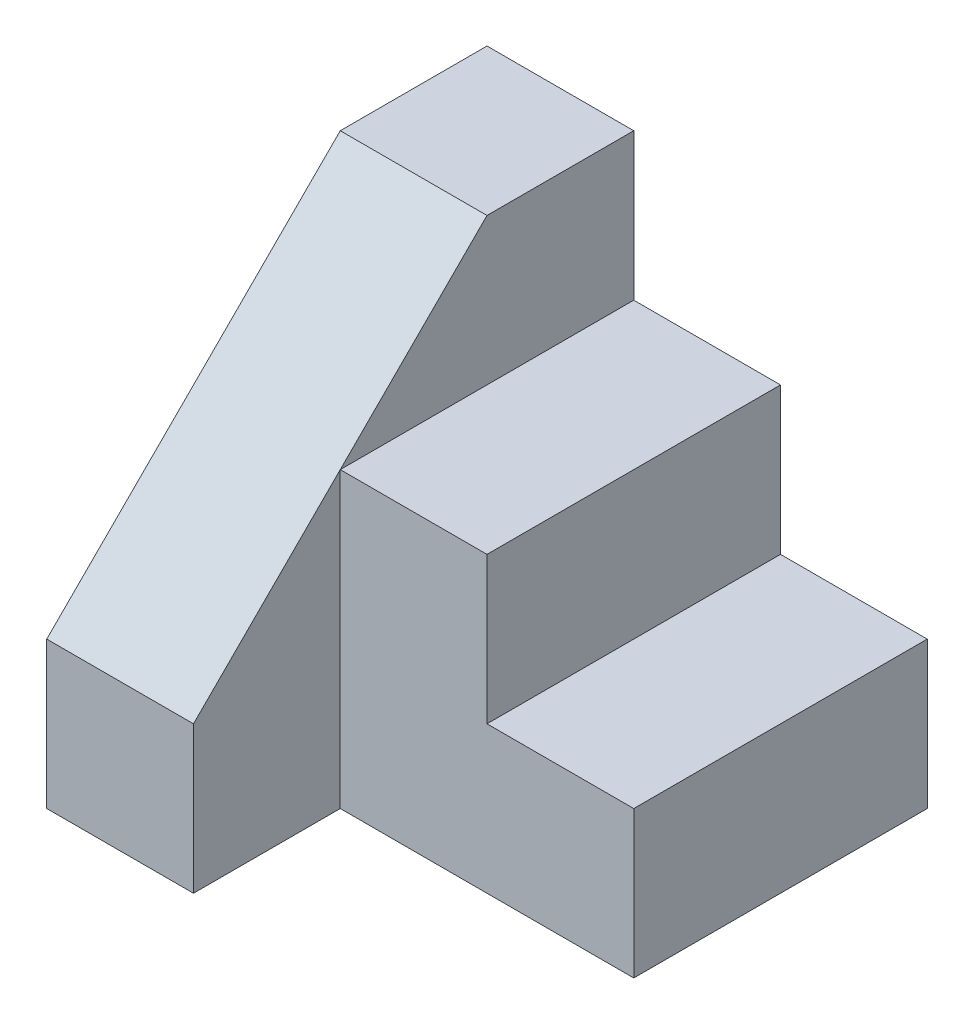
SolidWorks part; units mm, degrees
ref_plane "前基準面" through (0, 0, 0) normal (0, 0, 1) x (1, 0, 0)
ref_plane "上基準面" through (0, 0, 0) normal (0, 1, 0) x (1, 0, 0)
ref_plane "右基準面" through (0, 0, 0) normal (1, 0, 0) x (0, 0, -1)
sketch "草圖1" plane through (0, 0, 0) normal (0, 0, 1) x (1, 0, 0)
  line L1 (0, 0) -> (30, 0)
  line L2 (0, 0) -> (0, 30)
  line L3 (0, 30) -> (30, 30)
  line L4 (30, 0) -> (30, 30)
  dimension "D1" = 30
  dimension "D2" = 30
extrude "填料-伸1" add sketch "草圖1" against normal blind 30
sketch "草圖11" plane through (0, 0, 0) normal (0, 0, 1) x (1, 0, 0)
  line L0 (0, 10) -> (10, 10)
  line L1 (10, 10) -> (10, 20)
  line L2 (10, 20) -> (20, 20)
  line L3 (20, 20) -> (20, 10)
  line L4 (0, 30) -> (0, 0)
  line L5 (0, 0) -> (30, 0)
  line L6 (30, 0) -> (30, 30)
  line L7 (30, 30) -> (0, 30)
  line L8 (0, 30) -> (0, 0)
  line L9 (0, 0) -> (30, 0)
  line L10 (30, 0) -> (30, 30)
  line L11 (30, 30) -> (0, 30)
  line L12 (20, 10) -> (30, 10)
  line L13 (10, 20) -> (10, 30)
  line M11 (30, 30) -> (0, 30)
  dimension "D2" = 10
  dimension "D3" = 10
  dimension "D4" = 10
  dimension "D5" = 10
  dimension "D6" = 10
  dimension "D7" = 10
  dimension "D1" = 0
extrude "除料-伸長8" cut sketch "草圖11" against normal through all contours L13 L2 L3 L12 L10 M11
sketch "草圖16" plane through (0, 10, 0) normal (0, 1, 0) x (1, 0, 0)
  line L1 (30, 0) -> (10, 0)
  line L2 (30, 0) -> (30, 10)
  line L3 (30, 10) -> (10, 10)
  line L4 (10, 0) -> (10, 10)
  dimension "D1" = 20
  dimension "D2" = 10
extrude "除料-伸長9" cut sketch "草圖16" against normal through all both and the other way through all
sketch "草圖20" plane through (30, 0, 0) normal (1, 0, 0) x (0, 0, -1)
  line L0 (0, 0) -> (0, 30) construction
  line L1 (0, 0) -> (0, 30)
  line L2 (30, 30) -> (0, 30) construction
  line L3 (30, 30) -> (0, 30)
  line L4 (10, 10) -> (10, 0)
  line L5 (10, 0) -> (30, 0)
  line L6 (30, 0) -> (30, 10)
  line L7 (30, 10) -> (10, 10)
  line L8 (10, 10) -> (10, 0)
  line L9 (10, 0) -> (30, 0)
  line L10 (30, 0) -> (30, 10)
  line L11 (30, 10) -> (10, 10)
  line L12 (20, 30) -> (0, 10)
  dimension "D2" = 20
  dimension "D3" = 20
  dimension "D1" = 0
extrude "除料-伸長10" cut sketch "草圖20" against normal through all contours L12 L3 L1
